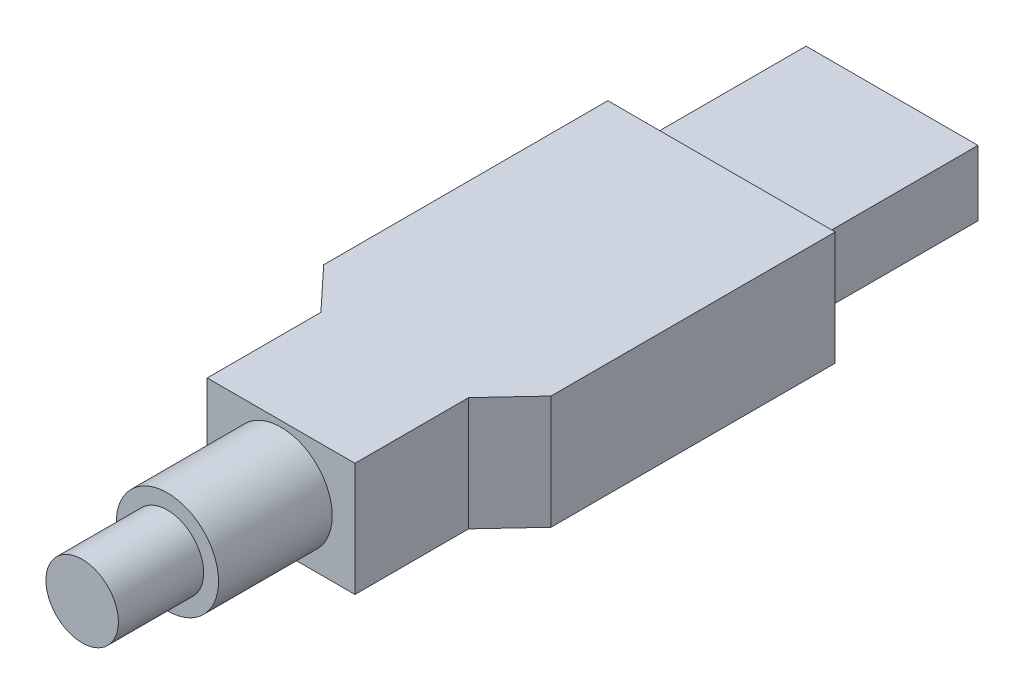
SolidWorks part; units mm, degrees
ref_plane "Plan de face" through (0, 0, 0) normal (0, 0, 1) x (1, 0, 0)
ref_plane "Plan de dessus" through (0, 0, 0) normal (0, 1, 0) x (1, 0, 0)
ref_plane "Plan de droite" through (0, 0, 0) normal (1, 0, 0) x (0, 0, -1)
sketch "Esquisse1" plane through (0, 0, 0) normal (0, 0, 1) x (1, 0, 0)
  line L1 (-6.05, 2.3) -> (6.05, 2.3)
  line L2 (-6.05, 2.3) -> (-6.05, -2.3)
  line L3 (-6.05, -2.3) -> (6.05, -2.3)
  line L4 (6.05, 2.3) -> (6.05, -2.3)
  point P4 (0, 2.3)
  point P6 (-6.05, 0)
  dimension "D1" = 12.1
  dimension "D2" = 4.6
extrude "Boss.-Extru.1" add sketch "Esquisse1" along normal blind 12
sketch "Esquisse3" plane through (0, 0, 0) normal (0, 0, -1) x (-1, 0, 0)
  line L0 (-6.05, 2.3) -> (6.05, 2.3) construction
  line L1 (-5.75, 0.3) -> (5.75, 0.3)
  line L2 (-5.75, 0.3) -> (-5.75, -2)
  line L3 (-5.75, -2) -> (5.75, -2)
  line L4 (5.75, 0.3) -> (5.75, -2)
  line L5 (6.05, -2.3) -> (-6.05, -2.3) construction
  line L6 (-6.05, -2.3) -> (-6.05, 2.3) construction
  point P8 (0, 0.3)
  dimension "D1" = 2
  dimension "D2" = 0.3
  dimension "D3" = 0.3
extrude "Enlèv. mat.-Extru.1" cut sketch "Esquisse3" against normal blind 9.6
sketch "Esquisse2" plane through (0, 0, 12) normal (0, 0, 1) x (1, 0, 0)
  line L1 (-8, 4) -> (8, 4)
  line L2 (-8, 4) -> (-8, -4)
  line L3 (-8, -4) -> (8, -4)
  line L4 (8, 4) -> (8, -4)
  point P4 (0, 4)
  point P6 (-8, 0)
  dimension "D1" = 16
  dimension "D2" = 8
extrude "Boss.-Extru.2" add sketch "Esquisse2" along normal blind 31
sketch "Esquisse4" plane through (0, 4, 0) normal (0, 1, 0) x (1, 0, 0)
  line L0 (-8, -43) -> (-8, -32)
  line L1 (-8, -43) -> (-8, -12) construction
  line L2 (-8, -32) -> (-5.2, -35)
  line L3 (-5.2, -35) -> (-5.2, -43)
  line L4 (8, -43) -> (-8, -43) construction
  line L5 (-5.2, -43) -> (-8, -43)
  line L6 (0, 0) -> (0, -3.7606) construction
  line L7 (6.05, 0) -> (-6.05, 0) construction
  line L8 (5.2, -43) -> (8, -43)
  line L9 (5.2, -35) -> (5.2, -43)
  line L10 (8, -32) -> (5.2, -35)
  line L11 (8, -43) -> (8, -32)
  dimension "D1" = 11
  dimension "D2" = 2.8
  dimension "D3" = 3
extrude "Enlèv. mat.-Extru.2" cut sketch "Esquisse4" against normal through all
sketch "Esquisse5" plane through (0, 0, 43) normal (0, 0, 1) x (1, 0, 0)
  circle A0 centre (0, 0) radius 3.6
  dimension "D1" = 7.2
extrude "Boss.-Extru.3" add sketch "Esquisse5" along normal blind 8
sketch "Esquisse6" plane through (0, 0, 51) normal (0, 0, 1) x (1, 0, 0)
  circle A0 centre (0, 0) radius 2.55
  dimension "D1" = 5.1
extrude "Boss.-Extru.4" add sketch "Esquisse6" along normal blind 6
equation "\"D3@Esquisse3\"=\"D2@Esquisse3\""
